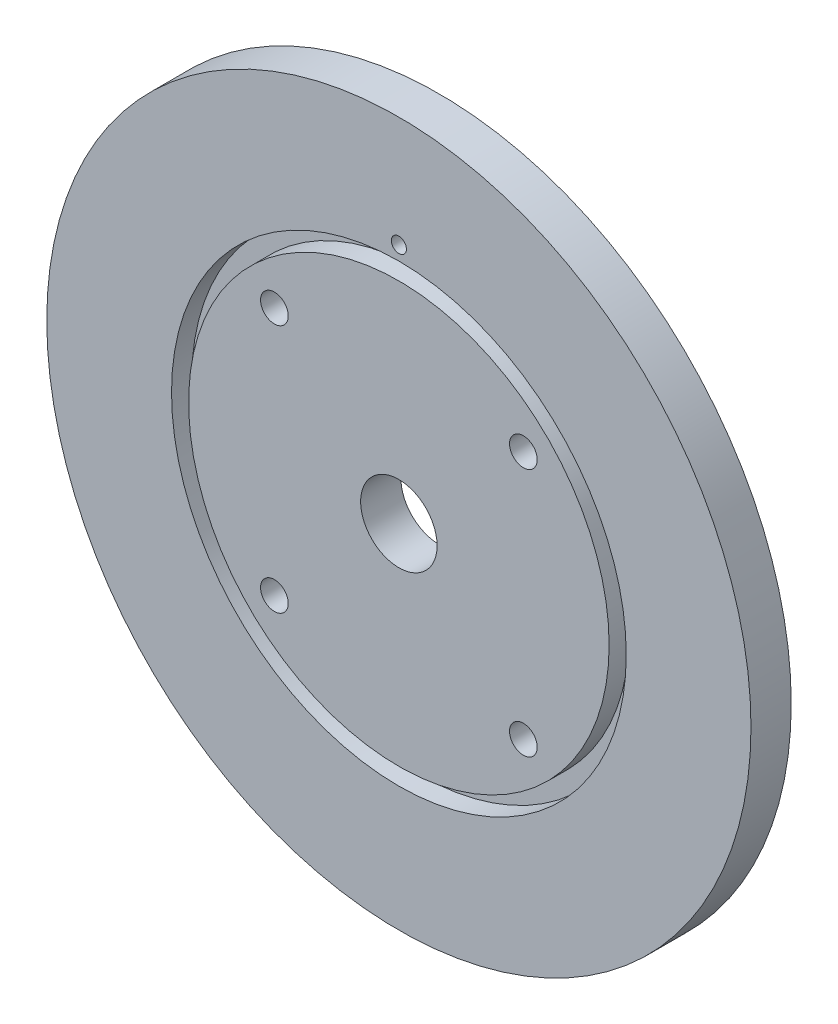
SolidWorks part; units mm, degrees
ref_plane "前视基准面" through (0, 0, 0) normal (0, 0, 1) x (1, 0, 0)
ref_plane "上视基准面" through (0, 0, 0) normal (0, 1, 0) x (1, 0, 0)
ref_plane "右视基准面" through (0, 0, 0) normal (1, 0, 0) x (0, 0, -1)
other "Configuration Table"
sketch "草图1" plane through (0, 0, 0) normal (0, 0, 1) x (1, 0, 0)
  circle A0 centre (0, 0) radius 70
  circle A1 centre (0, 0) radius 7.6
  circle A2 centre (24.7487, 24.7487) radius 2.75
  circle A3 centre (-24.7487, 24.7487) radius 2.75
  circle A4 centre (-24.7487, -24.7487) radius 2.75
  circle A5 centre (24.7487, -24.7487) radius 2.75
  circle A6 centre (0, 48) radius 1.5
extrude "凸台-拉伸1" add sketch "草图1" against normal blind 8
sketch "草图2" plane through (0, 0, 0) normal (0, 0, 1) x (1, 0, 0)
  circle A0 centre (0, 0) radius 45.2
  circle A1 centre (0, 0) radius 41.8
extrude "切除-拉伸2" cut sketch "草图2" against normal blind 4
